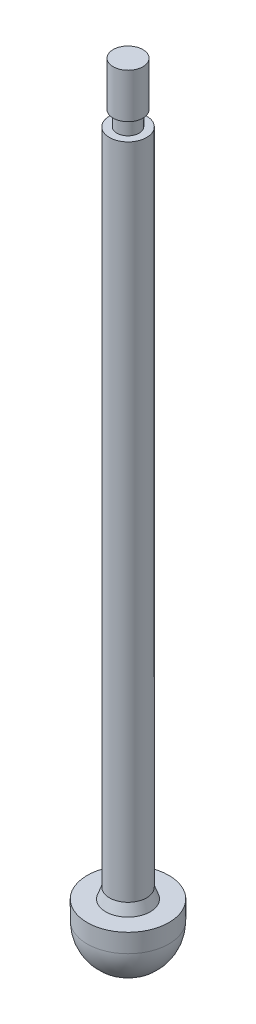
SolidWorks part; units mm, degrees
ref_plane "Front Plane" through (0, 0, 0) normal (0, 0, 1) x (1, 0, 0)
ref_plane "Top Plane" through (0, 0, 0) normal (0, 1, 0) x (1, 0, 0)
ref_plane "Right Plane" through (0, 0, 0) normal (1, 0, 0) x (0, 0, -1)
sketch "Sketch1" plane through (0, 0, 0) normal (0, 0, 1) x (1, 0, 0)
  line L0 (0, 0) -> (0, 100.5) construction
  line L1 (0, 0) -> (0, -5.5) construction
  line L2 (5.5, 0) -> (5.5, 2.5)
  line L3 (5.5, 2.5) -> (3, 2.5)
  line L4 (2.5, 3.8737) -> (2.5, 92.5)
  line L5 (2.5, 92.5) -> (1.5, 92.5)
  line L7 (2, 100.5) -> (0, 100.5)
  line L8 (0, 100.5) -> (0, -5.5)
  line L12 (2.5, 3.8737) -> (3, 2.5)
  line L13 (1.5, 92.5) -> (1.5, 94.5)
  line L14 (1.5, 94.5) -> (2, 94.5)
  line L15 (2, 94.5) -> (2, 100.5)
  arc A0 (0, -5.5) -> (5.5, 0) centre (0, 0) ccw
  point P12 (1.8483, 100.4231)
  point P15 (0, 100.2541)
  dimension "D1" = 5.5
  dimension "D2" = 2.5
  dimension "D3" = 8
  dimension "D4" = 2
  dimension "D5" = 8
  dimension "D6" = 3
  dimension "D7" = 110
  dimension "D8" = 90
  dimension "D9" = 2
  dimension "D10" = 1.5
revolve "Revolve1" add sketch "Sketch1" angle 360 about L0
ref_point "Point1"
